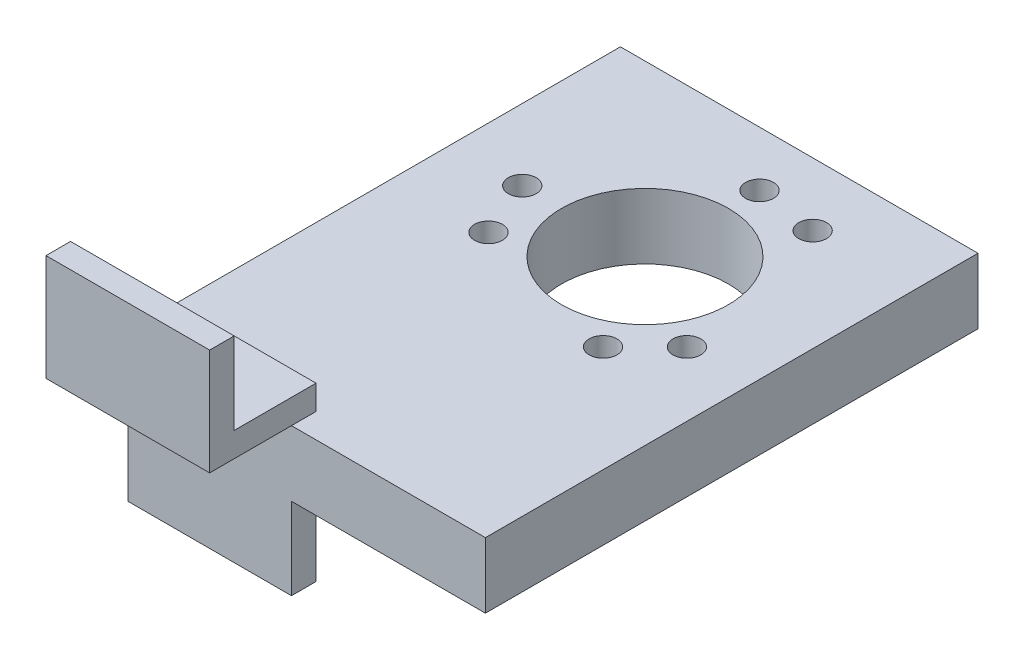
SolidWorks part; units mm, degrees
ref_plane "Front Plane" through (0, 0, 0) normal (0, 0, 1) x (1, 0, 0)
ref_plane "Top Plane" through (0, 0, 0) normal (0, 1, 0) x (1, 0, 0)
ref_plane "Right Plane" through (0, 0, 0) normal (1, 0, 0) x (0, 0, -1)
sketch "Sketch1" plane through (0, 0, 0) normal (0, 1, 0) x (1, 0, 0)
  line L0 (0, 0) -> (0, 39.5)
  line L1 (20, 0) -> (0, 0)
  line L2 (-23.7, 0) -> (0, 0)
  line L3 (0, 39.5) -> (0, 53.5)
  line L4 (0, 39.5) -> (-12.1244, 32.5)
  line L5 (0, 39.5) -> (12.1244, 32.5)
  line L6 (0, 39.5) -> (7.5, 52.4904)
  line L7 (0, 39.5) -> (-15, 39.5)
  line L8 (0, 39.5) -> (7, 27.3756)
  line L9 (15, 39.5) -> (20, 39.5)
  line L10 (20, 39.5) -> (20, 0)
  line L11 (0, 55.2) -> (0, 60.2)
  line L12 (20, 39.5) -> (20, 60.2)
  line L13 (20, 60.2) -> (0, 60.2)
  line L14 (-23.7, 0) -> (-23.7, 60.2)
  line L15 (-23.7, 60.2) -> (0, 60.2)
  circle A0 centre (0, 39.5) radius 10.2
  circle A1 centre (0, 39.5) radius 14
  circle A2 centre (0, 39.5) radius 15
  circle A3 centre (0, 53.5) radius 1.7
  circle A4 centre (7.5, 52.4904) radius 1.7
  circle A5 centre (12.1244, 32.5) radius 1.7
  circle A6 centre (7, 27.3756) radius 1.7
  circle A7 centre (-15, 39.5) radius 1.7
  circle A8 centre (-12.1244, 32.5) radius 1.7
extrude "Boss-Extrude2" add sketch "Sketch1" along normal blind 8 contours A4 A2 A3 A1 | A7 A1 A3 A2 | A8 A1 A7 A2 | A5 A2 A4 A1 | A8 A2 L0 A1 | A6 A1 L0 A2 | A6 A2 A5 A1 | A8 L4 A0 L7 A7 A1 | A7 L7 A0 L3 A3 A1 | A4 A1 A3 L3 A0 L6 | A5 A1 A4 L6 A0 L5 | A6 A1 A5 L5 A0 L8 | A6 L8 A0 L0 A1 | A8 A1 L0 A0 L4 | A8 A2 A7 A3 L11 L15 L14 L2 L0 | A4 A2 L9 L12 L13 L11 A3 | A6 A2 L0 L1 L10 L9 A5
sketch "Sketch2" plane through (0, 0, 0) normal (0, -1, 0) x (1, 0, 0)
  line L0 (-23.7, 0) -> (20, 0) construction
  line L1 (-23.7, 0) -> (-3.7, 0)
  line L2 (-23.7, 0) -> (-23.7, -3)
  line L3 (-23.7, -3) -> (-3.7, -3)
  line L4 (-3.7, 0) -> (-3.7, -3)
  line L5 (-23.7, 0) -> (-23.7, -60.2) construction
extrude "Boss-Extrude3" add sketch "Sketch2" along normal blind 10
sketch "Sketch3" plane through (0, 8, 0) normal (0, 1, 0) x (1, 0, 0)
  line L1 (-23.7, 0) -> (-3.7, 0)
  line L2 (-23.7, 0) -> (-23.7, 3)
  line L3 (-23.7, 3) -> (-3.7, 3)
  line L4 (-3.7, 0) -> (-3.7, 3)
extrude "Boss-Extrude4" add sketch "Sketch3" along normal blind 3
sketch "Sketch5" plane through (0, 0, 0) normal (0, 0, 1) x (1, 0, 0)
  line L1 (-23.7, 11) -> (-3.7, 11)
  line L2 (-23.7, 11) -> (-23.7, 8)
  line L3 (-23.7, 8) -> (-3.7, 8)
  line L4 (-3.7, 11) -> (-3.7, 8)
extrude "Boss-Extrude5" add sketch "Sketch5" along normal blind 10
sketch "Sketch6" plane through (0, 11, 0) normal (0, 1, 0) x (1, 0, 0)
  line L0 (-3.7, -10) -> (-3.7, 3) construction
  line L1 (-23.7, -10) -> (-3.7, -10)
  line L2 (-23.7, -10) -> (-23.7, -7)
  line L3 (-23.7, -7) -> (-3.7, -7)
  line L4 (-3.7, -10) -> (-3.7, -7)
extrude "Boss-Extrude6" add sketch "Sketch6" along normal blind 10
